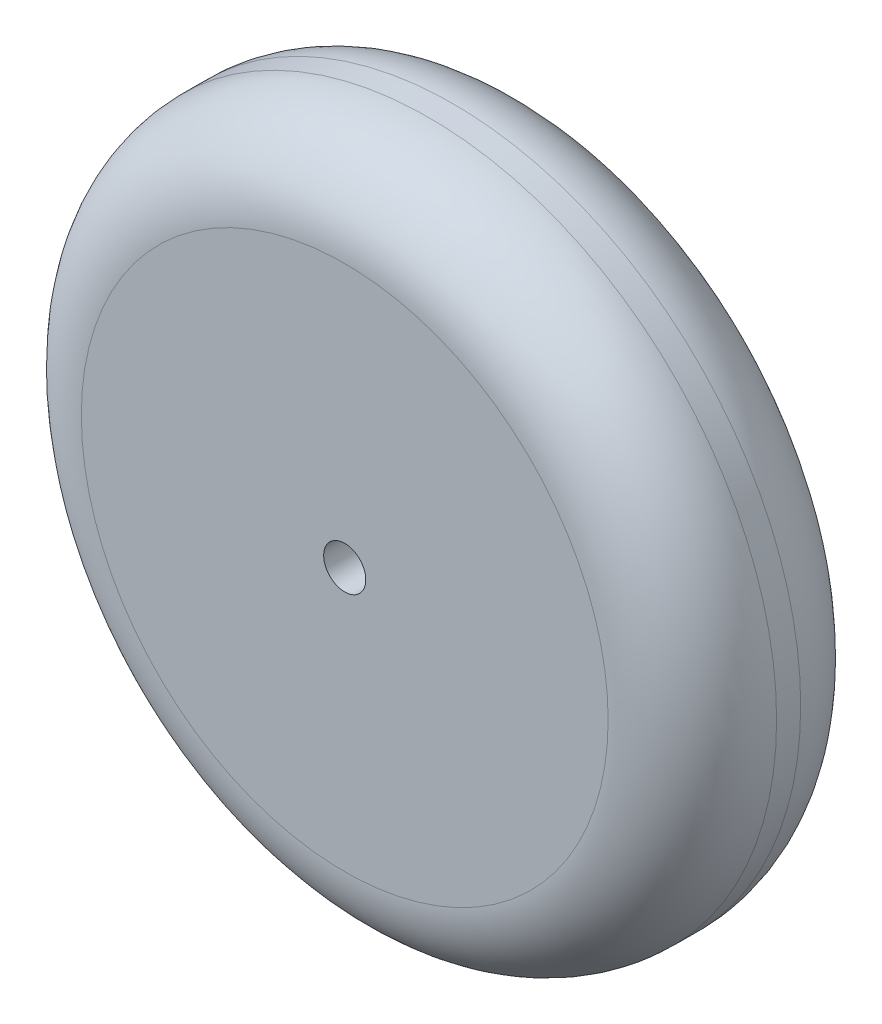
SolidWorks part; units mm, degrees
ref_plane "Front Plane" through (0, 0, 0) normal (0, 0, 1) x (1, 0, 0)
ref_plane "Top Plane" through (0, 0, 0) normal (0, 1, 0) x (1, 0, 0)
ref_plane "Right Plane" through (0, 0, 0) normal (1, 0, 0) x (0, 0, -1)
sketch "Sketch1" plane through (0, 0, 0) normal (0, 0, 1) x (1, 0, 0)
  circle A0 centre (0, 0) radius 41.275
  dimension "D1" = 82.55
extrude "Boss-Extrude1" add sketch "Sketch1" along normal blind 22.86
sketch "Sketch2" plane through (0, 0, 0) normal (0, 0, 1) x (1, 0, 0)
  circle A0 centre (0, 0) radius 2.5
  dimension "D1" = 5
extrude "Cut-Extrude1" cut sketch "Sketch2" along normal up to next
fillet "Fillet2" radius 10 2 edges at (41.275, 0, 22.86) (41.275, 0, 0)
